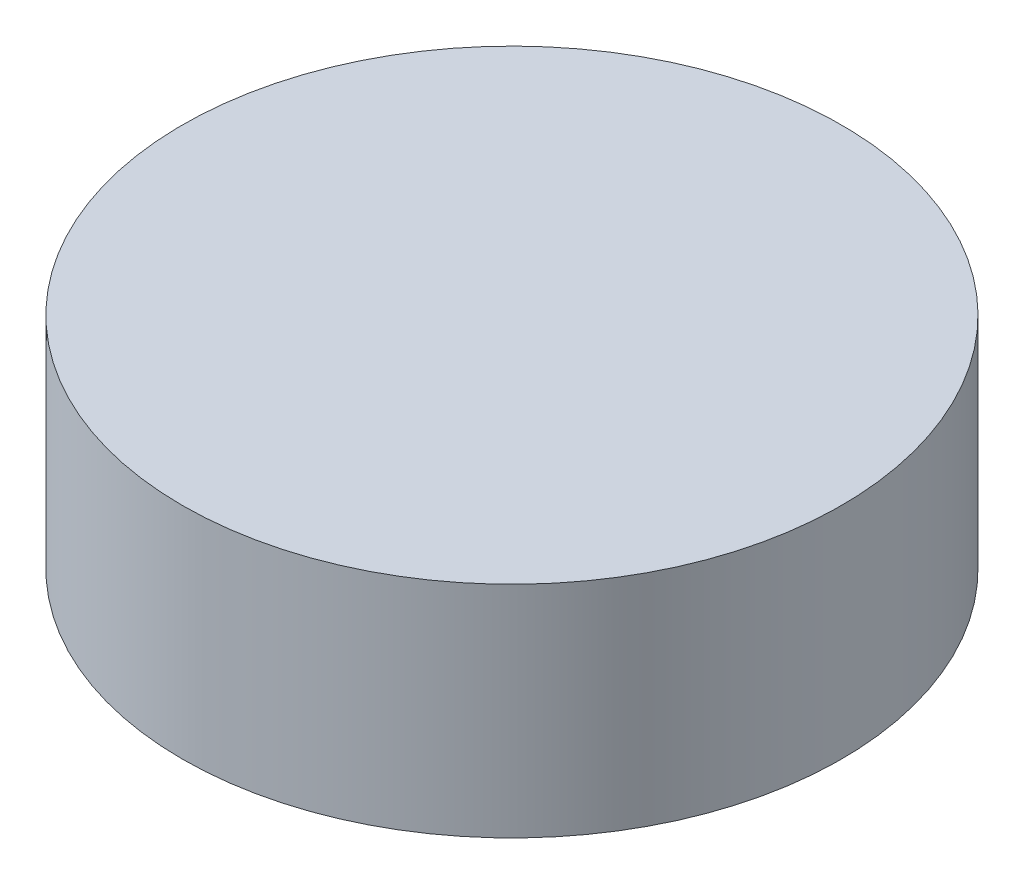
SolidWorks part; units mm, degrees
material "Gray Cast Iron"
ref_plane "Front Plane" through (0, 0, 0) normal (0, 0, 1) x (1, 0, 0)
ref_plane "Top Plane" through (0, 0, 0) normal (0, 1, 0) x (1, 0, 0)
ref_plane "Right Plane" through (0, 0, 0) normal (1, 0, 0) x (0, 0, -1)
sketch "Sketch1" plane through (0, 0, 0) normal (0, 1, 0) x (1, 0, 0)
  circle A0 centre (0, 0) radius 1.5
  dimension "D1" = 3
extrude "Boss-Extrude1" add sketch "Sketch1" along normal blind 1
